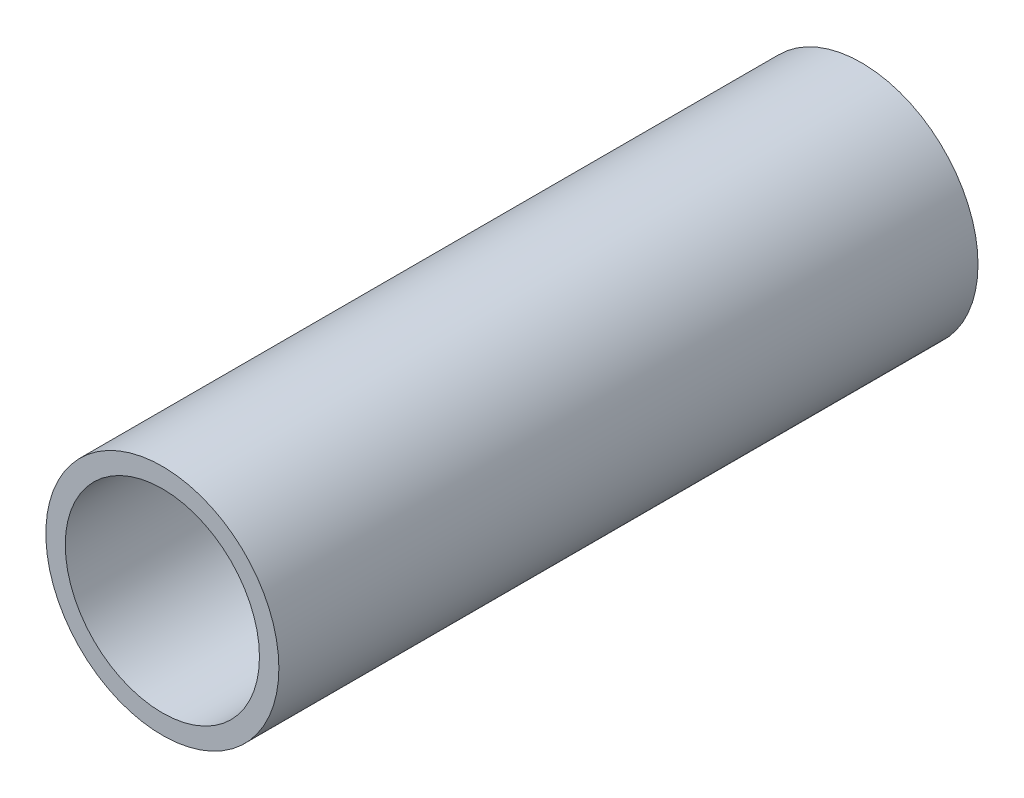
SolidWorks part; units mm, degrees
material "ABS PC"
ref_plane "前视基准面" through (0, 0, 0) normal (0, 0, 1) x (1, 0, 0)
ref_plane "上视基准面" through (0, 0, 0) normal (0, 1, 0) x (1, 0, 0)
ref_plane "右视基准面" through (0, 0, 0) normal (1, 0, 0) x (0, 0, -1)
sketch "草图1" plane through (0, 0, 0) normal (0, 0, 1) x (1, 0, 0)
  circle A0 centre (0, 0) radius 3
  circle A1 centre (0, 0) radius 2.5
  dimension "D1" = 6
  dimension "D2" = 5
extrude "凸台-拉伸1" add sketch "草图1" along normal blind 18
